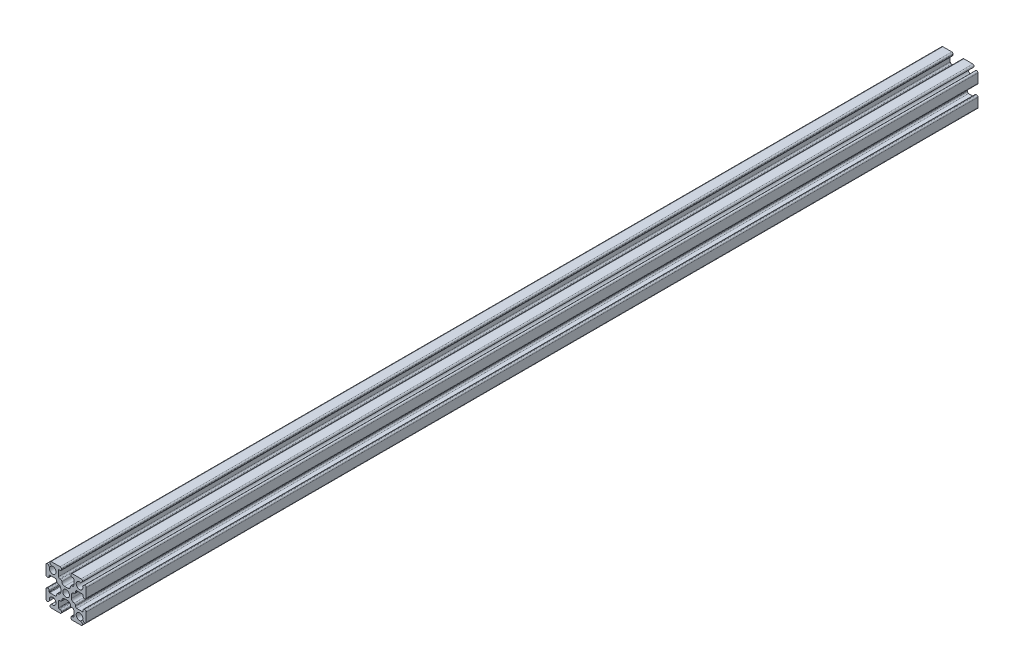
SolidWorks part; units mm, degrees
ref_plane "Front" through (0, 0, 0) normal (0, 0, 1) x (1, 0, 0)
ref_plane "Top" through (0, 0, 0) normal (0, 1, 0) x (1, 0, 0)
ref_plane "Right" through (0, 0, 0) normal (1, 0, 0) x (0, 0, -1)
sketch "Sketch1" plane through (0, 0, 0) normal (0, 0, 1) x (1, 0, 0)
  line L0 (6.6464, 5.9393) -> (6.1636, 5.4565)
  line L1 (5.4565, 6.1636) -> (5.9393, 6.6464)
  line L2 (5.5858, 7.5) -> (2.25, 7.5)
  line L3 (1.75, 7) -> (1.75, 6.8)
  line L4 (2.25, 6.3) -> (2.65, 6.3)
  line L5 (2.85, 6.1) -> (2.85, 4)
  line L6 (2.35, 3.5) -> (2.1, 3.5)
  line L7 (0.6, 2) -> (-0.6, 2)
  line L8 (-2.1, 3.5) -> (-2.35, 3.5)
  line L9 (-2.85, 4) -> (-2.85, 6.1)
  line L10 (-2.65, 6.3) -> (-2.25, 6.3)
  line L11 (-1.75, 6.8) -> (-1.75, 7)
  line L12 (-2.25, 7.5) -> (-5.5858, 7.5)
  line L13 (-5.9393, 6.6464) -> (-5.4565, 6.1636)
  line L14 (-6.1636, 5.4565) -> (-6.6464, 5.9393)
  line L15 (-7.5, 5.5858) -> (-7.5, 2.25)
  line L16 (-7, 1.75) -> (-6.8, 1.75)
  line L17 (-6.3, 2.25) -> (-6.3, 2.65)
  line L18 (-6.1, 2.85) -> (-4, 2.85)
  line L19 (-3.5, 2.35) -> (-3.5, 2.1)
  line L20 (-2, 0.6) -> (-2, -0.6)
  line L21 (-3.5, -2.1) -> (-3.5, -2.35)
  line L22 (-4, -2.85) -> (-6.1, -2.85)
  line L23 (-6.3, -2.65) -> (-6.3, -2.25)
  line L24 (-6.8, -1.75) -> (-7, -1.75)
  line L25 (-7.5, -2.25) -> (-7.5, -5.5858)
  line L26 (-6.6464, -5.9393) -> (-6.1636, -5.4565)
  line L27 (-5.4565, -6.1636) -> (-5.9393, -6.6464)
  line L28 (-5.5858, -7.5) -> (-2.25, -7.5)
  line L29 (-1.75, -7) -> (-1.75, -6.8)
  line L30 (-2.25, -6.3) -> (-2.65, -6.3)
  line L31 (-2.85, -6.1) -> (-2.85, -4)
  line L32 (-2.35, -3.5) -> (-2.1, -3.5)
  line L33 (-0.6, -2) -> (0.6, -2)
  line L34 (2.1, -3.5) -> (2.35, -3.5)
  line L35 (2.85, -4) -> (2.85, -6.1)
  line L36 (2.65, -6.3) -> (2.25, -6.3)
  line L37 (1.75, -6.8) -> (1.75, -7)
  line L38 (2.25, -7.5) -> (5.5858, -7.5)
  line L39 (5.9393, -6.6464) -> (5.4565, -6.1636)
  line L40 (6.1636, -5.4565) -> (6.6464, -5.9393)
  line L41 (7.5, -5.5858) -> (7.5, -2.25)
  line L42 (7, -1.75) -> (6.8, -1.75)
  line L43 (6.3, -2.25) -> (6.3, -2.65)
  line L44 (6.1, -2.85) -> (4, -2.85)
  line L45 (3.5, -2.35) -> (3.5, -2.1)
  line L46 (2, -0.6) -> (2, 0.6)
  line L47 (3.5, 2.1) -> (3.5, 2.35)
  line L48 (4, 2.85) -> (6.1, 2.85)
  line L49 (6.3, 2.65) -> (6.3, 2.25)
  line L50 (6.8, 1.75) -> (7, 1.75)
  line L51 (7.5, 2.25) -> (7.5, 5.5858)
  circle A0 centre (0, 0) radius 1.25
  arc A1 (6.1636, 5.4565) -> (5.4565, 6.1636) centre (5, 5) cw
  arc A2 (5.9393, 6.6464) -> (5.5858, 7.5) centre (5.5858, 7) ccw
  arc A3 (2.25, 7.5) -> (1.75, 7) centre (2.25, 7) ccw
  arc A4 (1.75, 6.8) -> (2.25, 6.3) centre (2.25, 6.8) ccw
  arc A5 (2.65, 6.3) -> (2.85, 6.1) centre (2.65, 6.1) cw
  arc A6 (2.85, 4) -> (2.35, 3.5) centre (2.35, 4) cw
  arc A7 (2.1, 3.5) -> (1.6, 3) centre (2.1, 3) ccw
  arc A8 (1.6, 3) -> (0.6, 2) centre (0.6, 3) cw
  arc A9 (-0.6, 2) -> (-1.6, 3) centre (-0.6, 3) cw
  arc A10 (-1.6, 3) -> (-2.1, 3.5) centre (-2.1, 3) ccw
  arc A11 (-2.35, 3.5) -> (-2.85, 4) centre (-2.35, 4) cw
  arc A12 (-2.85, 6.1) -> (-2.65, 6.3) centre (-2.65, 6.1) cw
  arc A13 (-2.25, 6.3) -> (-1.75, 6.8) centre (-2.25, 6.8) ccw
  arc A14 (-1.75, 7) -> (-2.25, 7.5) centre (-2.25, 7) ccw
  arc A15 (-5.5858, 7.5) -> (-5.9393, 6.6464) centre (-5.5858, 7) ccw
  arc A16 (-5.4565, 6.1636) -> (-6.1636, 5.4565) centre (-5, 5) cw
  arc A17 (-6.6464, 5.9393) -> (-7.5, 5.5858) centre (-7, 5.5858) ccw
  arc A18 (-7.5, 2.25) -> (-7, 1.75) centre (-7, 2.25) ccw
  arc A19 (-6.8, 1.75) -> (-6.3, 2.25) centre (-6.8, 2.25) ccw
  arc A20 (-6.3, 2.65) -> (-6.1, 2.85) centre (-6.1, 2.65) cw
  arc A21 (-4, 2.85) -> (-3.5, 2.35) centre (-4, 2.35) cw
  arc A22 (-3.5, 2.1) -> (-3, 1.6) centre (-3, 2.1) ccw
  arc A23 (-3, 1.6) -> (-2, 0.6) centre (-3, 0.6) cw
  arc A24 (-2, -0.6) -> (-3, -1.6) centre (-3, -0.6) cw
  arc A25 (-3, -1.6) -> (-3.5, -2.1) centre (-3, -2.1) ccw
  arc A26 (-3.5, -2.35) -> (-4, -2.85) centre (-4, -2.35) cw
  arc A27 (-6.1, -2.85) -> (-6.3, -2.65) centre (-6.1, -2.65) cw
  arc A28 (-6.3, -2.25) -> (-6.8, -1.75) centre (-6.8, -2.25) ccw
  arc A29 (-7, -1.75) -> (-7.5, -2.25) centre (-7, -2.25) ccw
  arc A30 (-7.5, -5.5858) -> (-6.6464, -5.9393) centre (-7, -5.5858) ccw
  arc A31 (-6.1636, -5.4565) -> (-5.4565, -6.1636) centre (-5, -5) cw
  arc A32 (-5.9393, -6.6464) -> (-5.5858, -7.5) centre (-5.5858, -7) ccw
  arc A33 (-2.25, -7.5) -> (-1.75, -7) centre (-2.25, -7) ccw
  arc A34 (-1.75, -6.8) -> (-2.25, -6.3) centre (-2.25, -6.8) ccw
  arc A35 (-2.65, -6.3) -> (-2.85, -6.1) centre (-2.65, -6.1) cw
  arc A36 (-2.85, -4) -> (-2.35, -3.5) centre (-2.35, -4) cw
  arc A37 (-2.1, -3.5) -> (-1.6, -3) centre (-2.1, -3) ccw
  arc A38 (-1.6, -3) -> (-0.6, -2) centre (-0.6, -3) cw
  arc A39 (0.6, -2) -> (1.6, -3) centre (0.6, -3) cw
  arc A40 (1.6, -3) -> (2.1, -3.5) centre (2.1, -3) ccw
  arc A41 (2.35, -3.5) -> (2.85, -4) centre (2.35, -4) cw
  arc A42 (2.85, -6.1) -> (2.65, -6.3) centre (2.65, -6.1) cw
  arc A43 (2.25, -6.3) -> (1.75, -6.8) centre (2.25, -6.8) ccw
  arc A44 (1.75, -7) -> (2.25, -7.5) centre (2.25, -7) ccw
  arc A45 (5.5858, -7.5) -> (5.9393, -6.6464) centre (5.5858, -7) ccw
  arc A46 (5.4565, -6.1636) -> (6.1636, -5.4565) centre (5, -5) cw
  arc A47 (6.6464, -5.9393) -> (7.5, -5.5858) centre (7, -5.5858) ccw
  arc A48 (7.5, -2.25) -> (7, -1.75) centre (7, -2.25) ccw
  arc A49 (6.8, -1.75) -> (6.3, -2.25) centre (6.8, -2.25) ccw
  arc A50 (6.3, -2.65) -> (6.1, -2.85) centre (6.1, -2.65) cw
  arc A51 (4, -2.85) -> (3.5, -2.35) centre (4, -2.35) cw
  arc A52 (3.5, -2.1) -> (3, -1.6) centre (3, -2.1) ccw
  arc A53 (3, -1.6) -> (2, -0.6) centre (3, -0.6) cw
  arc A54 (2, 0.6) -> (3, 1.6) centre (3, 0.6) cw
  arc A55 (3, 1.6) -> (3.5, 2.1) centre (3, 2.1) ccw
  arc A56 (3.5, 2.35) -> (4, 2.85) centre (4, 2.35) cw
  arc A57 (6.1, 2.85) -> (6.3, 2.65) centre (6.1, 2.65) cw
  arc A58 (6.3, 2.25) -> (6.8, 1.75) centre (6.8, 2.25) ccw
  arc A59 (7, 1.75) -> (7.5, 2.25) centre (7, 2.25) ccw
  arc A60 (7.5, 5.5858) -> (6.6464, 5.9393) centre (7, 5.5858) ccw
extrude "Boss-Extrude1" add sketch "Sketch1" along normal blind 332.35
